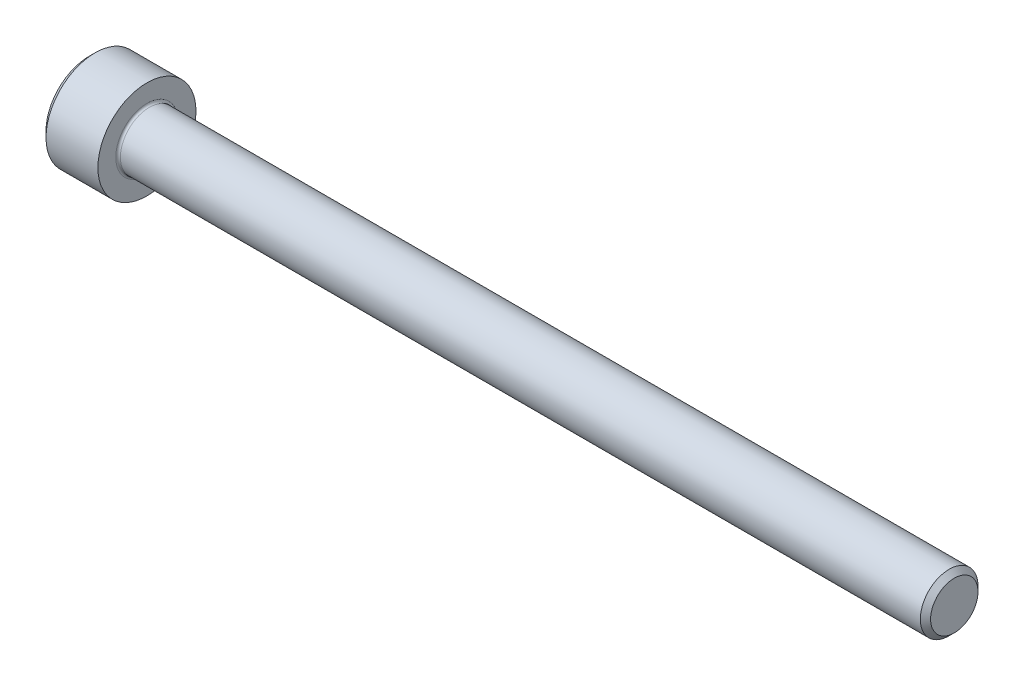
SolidWorks part; units mm, degrees
ref_plane "Plane1" through (0, 0, 0) normal (0, 0, 1) x (1, 0, 0)
ref_plane "Plane2" through (0, 0, 0) normal (0, 1, 0) x (1, 0, 0)
ref_plane "Plane3" through (0, 0, 0) normal (1, 0, 0) x (0, 0, -1)
sketch "BodySke" plane through (0, 0, 0) normal (0, 0, 1) x (1, 0, 0)
  line L0 (0, 0) -> (0, 3.75)
  line L1 (0.5, 4.25) -> (5, 4.25)
  line L2 (5, 4.25) -> (5, 2.5)
  line L3 (5, 2.5) -> (74.555, 2.5)
  line L4 (75, 2.055) -> (75, 0)
  line L5 (75, 0) -> (0, 0)
  line L6 (-31.75, 0) -> (127, 0) construction
  line L7 (0, 3.75) -> (0.5, 4.25)
  line L8 (75, 2.055) -> (74.555, 2.5)
  line L9 (0, -3.75) -> (0.5, -4.25) construction
  line L10 (75, -2.055) -> (74.555, -2.5) construction
  line L11 (5.8, 9.525) -> (5.8, 3.175) construction
  line L12 (53, 9.525) -> (53, 3.175) construction
  line L13 (25, 9.525) -> (25, 3.175) construction
  dimension "Diameter" = 5
  dimension "Head_ht" = 5
  dimension "Length" = 70
  dimension "Body_ch_ang" = 45
  dimension "Head_dia" = 8.5
  dimension "Head_ch_ang" = 45
  dimension "Minor_dia" = 4.11
  dimension "Advance" = 0.8
  dimension "Thread_nom" = 22
  dimension "Thread_length" = 50
  dimension "Head_ch_ht" = 0.5
revolve "Base-Revolve" add sketch "BodySke"
cosmetic thread "ThreadCosmetic"
fillet "Fillet1" radius 0.2 1 edges at (5, 0, 2.5)
sketch "Sketch2" plane through (0, 0, 0) normal (0, 0, 1) x (1, 0, 0)
  line L0 (0, 2.042) -> (2.5, 2.042)
  line L1 (2.5, 2.042) -> (3.6789, 0)
  line L2 (-31.75, 0) -> (127, 0) construction
  line L3 (3.6789, 0) -> (0, 0)
  line L4 (0, 0) -> (0, 2.042)
  line L5 (0, 3.75) -> (0, -3.75) construction
  line L6 (0, 0) -> (47.625, 0) construction
  line L7 (5, -4.25) -> (5, 4.25) construction
  dimension "D1" = 2.042
  dimension "D2" = 60
  dimension "Wall_thickness" = 2.5
revolve "Hex-PreBroach" cut sketch "Sketch2" angle 360 about L6
sketch "Sketch3" plane through (0, 0, 0) normal (-1, 0, 0) x (0, 0.5, 0.866)
  line L0 (1.1789, 2.042) -> (-1.1789, 2.042)
  line L1 (-1.1789, 2.042) -> (-2.3579, 0)
  line L2 (1.1789, 2.042) -> (2.3579, 0)
  line L3 (1.1789, -2.042) -> (2.3579, 0)
  line L4 (1.1789, -2.042) -> (-1.1789, -2.042)
  line L5 (-1.1789, -2.042) -> (-2.3579, 0)
  dimension "D1" = 2.042
  dimension "D2" = 2.042
  dimension "Hex_size" = 4.084
extrude "Hex" cut sketch "Sketch3" against normal blind 2.5
sketch "Sketch4" plane through (0, 0, 0) normal (-1, 0, 0) x (0, 0, 1)
  line L0 (0, 0) -> (2.3876, 0)
  line L1 (0, 0) -> (6.1484, 3.5498) construction
  line L2 (0, 0) -> (1.1938, 2.0677)
  line L3 (1.9883, 0.576) -> (2.2704, 0.7389)
  line L4 (1.493, 1.4339) -> (1.7751, 1.5968)
  arc A0 (1.9883, 0.576) -> (1.493, 1.4339) centre (0, 0) ccw
  arc A1 (2.3876, 0) -> (2.2704, 0.7389) centre (0, 0) ccw
  arc A2 (1.1938, 2.0677) -> (1.7751, 1.5968) centre (0, 0) cw
  dimension "D1" = 30
  dimension "Spline_n_dim" = 4.1402
  dimension "Spline_m_dim" = 4.7752
  dimension "D2" = 60
  dimension "D3" = 0.4953
  dimension "Spline_p_dim" = 0.9906
extrude "Spline" [suppressed] cut sketch "Sketch4" against normal blind 2.5
pattern_circular "CirPattern1" [suppressed] count 6 every 60
sketch "Sketch5" plane through (0, 0, 0) normal (0, 0, 1) x (1, 0, 0)
  line L0 (-31.75, 0) -> (127, 0) construction
  line L2 (0, 3.75) -> (0, -3.75) construction
  circle A0 centre (2, 0) radius 0.675
  dimension "Drilled_hole_dia" = 1.35
  dimension "Drilled_hole_loc" = 2
extrude "Hole" [suppressed] cut sketch "Sketch5" against normal through all and the other way through all
pattern_circular "Drilled-4" [suppressed] count 2 every 60
pattern_circular "Drilled-6" [suppressed] count 3 every 60
sketch "ThdSchSke" plane through (0, 0, 0) normal (0, 0, 1) x (1, 0, 0)
  line L0 (53, -2.055) -> (52.6884, -2.5)
  line L1 (53, -2.055) -> (53.3116, -2.5)
  line L2 (53.3116, -2.5) -> (53.3116, -3.125)
  line L3 (-3.175, 0) -> (5.1513, 0) construction
  line L5 (53.3116, -3.125) -> (52.6884, -3.125)
  line L6 (52.6884, -3.125) -> (52.6884, -2.5)
  line L7 (0, 3.75) -> (0, -3.75) construction
  dimension "Thread_minor" = 4.11
  dimension "Diameter" = 5
  dimension "Start" = 53
  dimension "SideAngle" = 55
  dimension "VeeAngle" = 70
  dimension "Overcut" = 6.25
revolve "ThreadSchematic" [suppressed] cut sketch "ThdSchSke" angle 360 about L3
pattern_linear "ThdSchPat" [suppressed]
equation "\"D2@Sketch3\" = \"Hex_size@Sketch3\" / 2"
equation "\"D1@Sketch3\" = \"Hex_size@Sketch3\" / 2"
equation "\"D1@Sketch2\" = \"Hex_size@Sketch3\" / 2"
equation "\"D3@Sketch4\" = \"Spline_p_dim@Sketch4\" / 2"
equation "\"Thread_minor@ThreadCosmetic\"  =  \"Minor_dia@BodySke\""
equation "\"D2@CirPattern1\" = 360 / \"Num_teeth@CirPattern1\""
equation "\"Wall_thickness@Sketch2\" = \"Head_ht@BodySke\" - \"Key_eng@Hex\""
equation "\"Thread_length@ThreadCosmetic\" = ((sgn( (\"Length@BodySke\" - \"Advance@BodySke\" ) - \"Thread_nom@BodySke\" )-1)*( (\"Length@BodySke\" - \"Advance@BodySke\" ) - \"Thread_nom@BodySke\" ))/-2+ \"Thread_nom@BodySke\""
equation "\"Thread_minor@ThdSchSke\" = \"Minor_dia@BodySke\""
equation "\"Diameter@ThdSchSke\" = \"Diameter@BodySke\""
equation "\"Overcut@ThdSchSke\" = \"Diameter@BodySke\" * 1.25"
equation "\"Start@ThdSchSke\" = \"Head_ht@BodySke\" + \"Length@BodySke\" - \"Thread_length@ThreadCosmetic\"  '---Non-countersunk---"
equation "\"Num_threads@ThdSchPat\" = int( \"Thread_length@ThreadCosmetic\" / \"Advance@BodySke\" + 0.999 )  + 1"
equation "\"Advance@ThdSchPat\" = \"Thread_length@ThreadCosmetic\" /  (\"Num_threads@ThdSchPat\" - 1) 'relax it"
equation "\"Num_threads@ThdSchPat\" = \"Num_threads@ThdSchPat\" - sgn( \"Num_threads@ThdSchPat\" - 1) '---chamfered tips only---"
